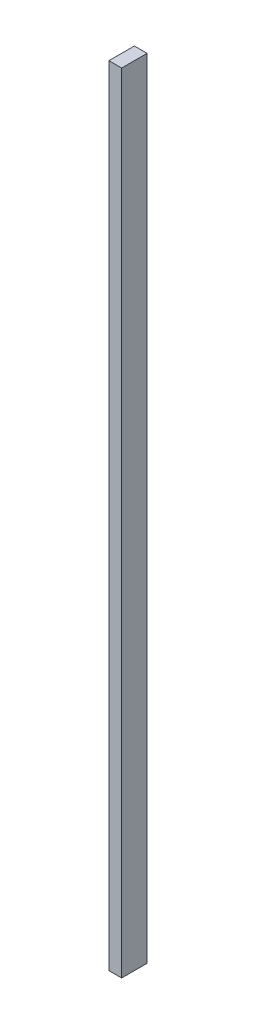
SolidWorks part; units mm, degrees
ref_plane "Спереди" through (0, 0, 0) normal (0, 0, 1) x (1, 0, 0)
ref_plane "Сверху" through (0, 0, 0) normal (0, 1, 0) x (1, 0, 0)
ref_plane "Справа" through (0, 0, 0) normal (1, 0, 0) x (0, 0, -1)
other "Configuration Table"
sketch "Эскиз1" plane through (0, 0, 0) normal (0, 1, 0) x (1, 0, 0)
  line L1 (12.5, 25) -> (-12.5, 25)
  line L2 (12.5, 25) -> (12.5, -25)
  line L3 (12.5, -25) -> (-12.5, -25)
  line L4 (-12.5, 25) -> (-12.5, -25)
  line L5 (12.5, 25) -> (-12.5, -25) construction
  line L6 (12.5, -25) -> (-12.5, 25) construction
  point P0 (0, 0)
extrude "Бобышка-Вытянуть1" add sketch "Эскиз1" along normal blind 1550
